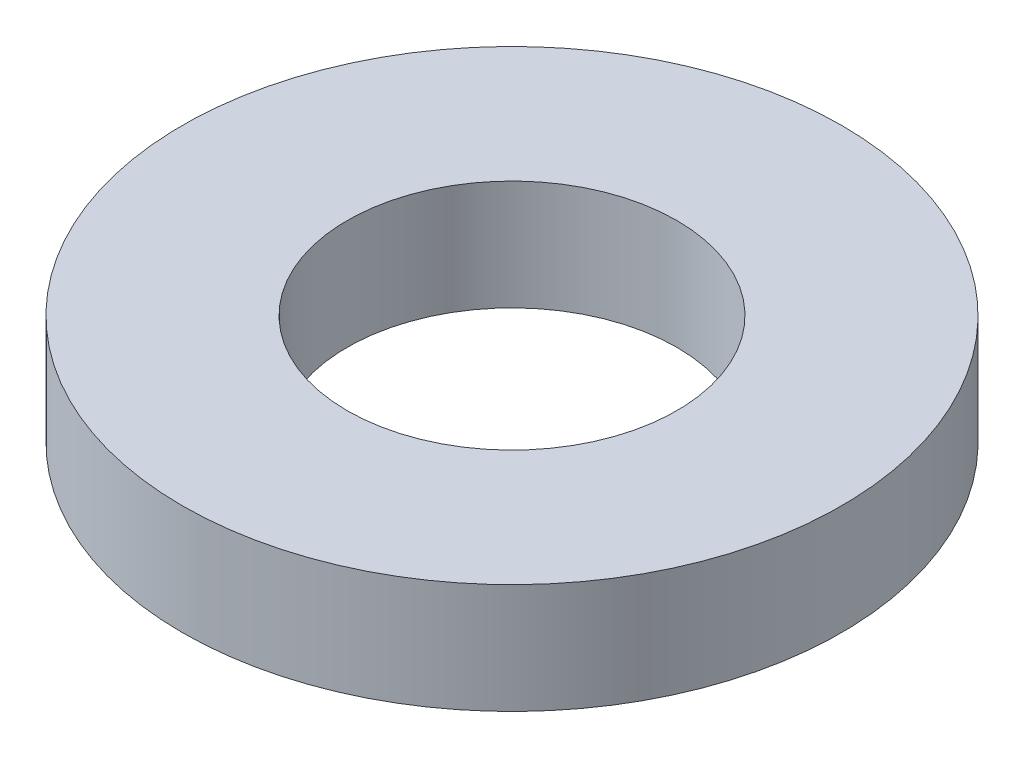
SolidWorks part; units mm, degrees
ref_plane "Front Plane" through (0, 0, 0) normal (0, 0, 1) x (1, 0, 0)
ref_plane "Top Plane" through (0, 0, 0) normal (0, 1, 0) x (1, 0, 0)
ref_plane "Right Plane" through (0, 0, 0) normal (1, 0, 0) x (0, 0, -1)
sketch "Sketch1" plane through (0, 0, 0) normal (0, 1, 0) x (1, 0, 0)
  circle A0 centre (0, 0) radius 15
  circle A1 centre (0, 0) radius 30
  dimension "D1" = 30
  dimension "D2" = 60
extrude "Boss-Extrude1" add sketch "Sketch1" along normal blind 10
